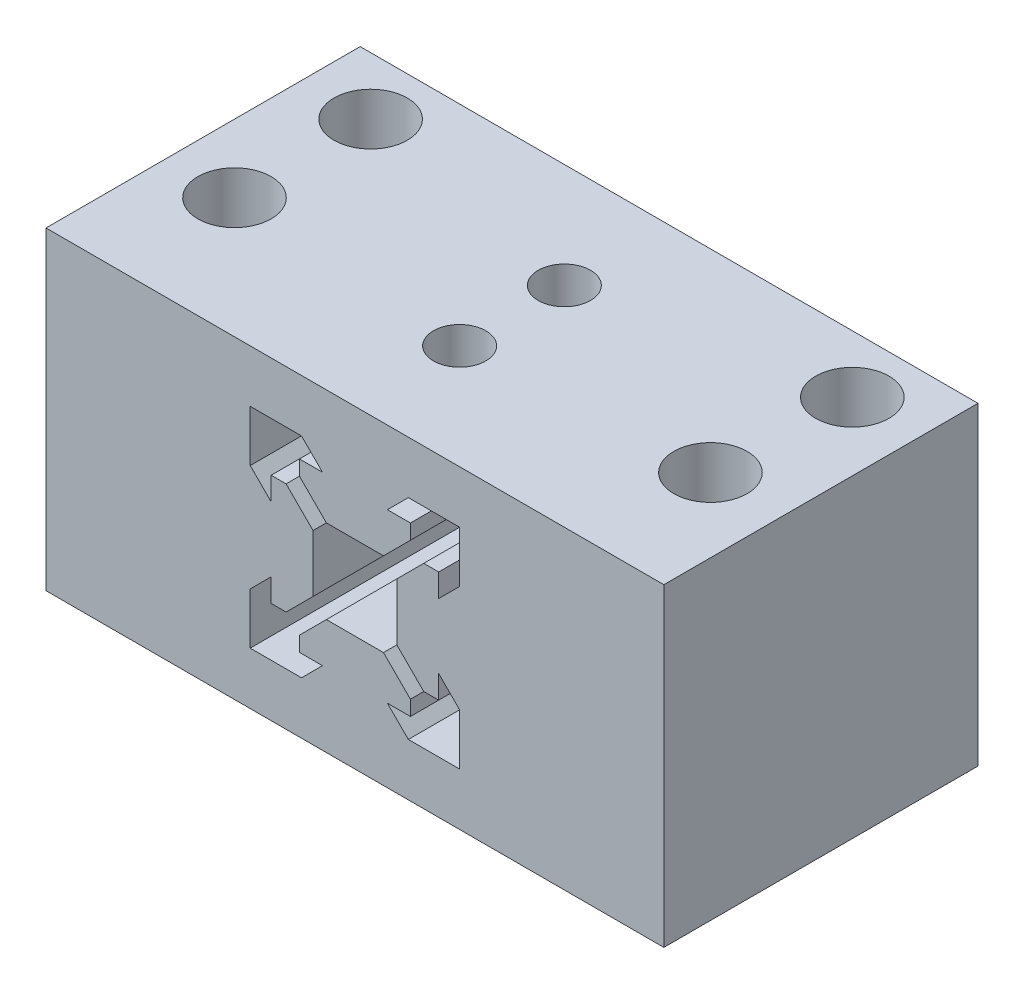
SolidWorks part; units mm, degrees
ref_plane "Front Plane" through (0, 0, 0) normal (0, 0, 1) x (1, 0, 0)
ref_plane "Top Plane" through (0, 0, 0) normal (0, 1, 0) x (1, 0, 0)
ref_plane "Right Plane" through (0, 0, 0) normal (1, 0, 0) x (0, 0, -1)
sketch "Sketch1" plane through (0, 0, 0) normal (0, 0, 1) x (1, 0, 0)
  line L1 (-29.5, 15) -> (29.5, 15)
  line L2 (-29.5, 15) -> (-29.5, -15)
  line L3 (-29.5, -15) -> (29.5, -15)
  line L4 (29.5, 15) -> (29.5, -15)
  line L5 (-29.5, 15) -> (29.5, -15) construction
  line L6 (-29.5, -15) -> (29.5, 15) construction
  line L90 (4, 2.7272) -> (6.5728, 5.3)
  line L91 (6.5728, 5.3) -> (8, 5.3)
  line L92 (8, 5.3) -> (8, 3.1)
  line L93 (8, 3.1) -> (10, 5.1)
  line L94 (10, 5.1) -> (10, 10)
  line L95 (10, 10) -> (5.1, 10)
  line L96 (5.1, 10) -> (3.1, 8)
  line L97 (3.1, 8) -> (5.3, 8)
  line L98 (5.3, 8) -> (5.3, 6.5728)
  line L99 (5.3, 6.5728) -> (2.7272, 4)
  line L100 (2.7272, 4) -> (-2.7272, 4)
  line L101 (-2.7272, 4) -> (-5.3, 6.5728)
  line L102 (-5.3, 6.5728) -> (-5.3, 8)
  line L103 (-5.3, 8) -> (-3.1, 8)
  line L104 (-3.1, 8) -> (-5.1, 10)
  line L105 (-5.1, 10) -> (-10, 10)
  line L106 (-10, 10) -> (-10, 5.1)
  line L107 (-10, 5.1) -> (-8, 3.1)
  line L108 (-8, 3.1) -> (-8, 5.3)
  line L109 (-8, 5.3) -> (-6.5728, 5.3)
  line L110 (-6.5728, 5.3) -> (-4, 2.7272)
  line L111 (-4, 2.7272) -> (-4, -2.7272)
  line L112 (-4, -2.7272) -> (-6.5728, -5.3)
  line L113 (-6.5728, -5.3) -> (-8, -5.3)
  line L114 (-8, -5.3) -> (-8, -3.1)
  line L115 (-8, -3.1) -> (-10, -5.1)
  line L116 (-10, -5.1) -> (-10, -10)
  line L117 (-10, -10) -> (-5.1, -10)
  line L118 (-5.1, -10) -> (-3.1, -8)
  line L119 (-3.1, -8) -> (-5.3, -8)
  line L120 (-5.3, -8) -> (-5.3, -6.5728)
  line L121 (-5.3, -6.5728) -> (-2.7272, -4)
  line L122 (-2.7272, -4) -> (2.7272, -4)
  line L123 (2.7272, -4) -> (5.3, -6.5728)
  line L124 (5.3, -6.5728) -> (5.3, -8)
  line L125 (5.3, -8) -> (3.1, -8)
  line L126 (3.1, -8) -> (5.1, -10)
  line L127 (5.1, -10) -> (10, -10)
  line L128 (10, -10) -> (10, -5.1)
  line L129 (10, -5.1) -> (8, -3.1)
  line L130 (8, -3.1) -> (8, -5.3)
  line L131 (8, -5.3) -> (6.5728, -5.3)
  line L132 (6.5728, -5.3) -> (4, -2.7272)
  line L133 (4, -2.7272) -> (4, 2.7272)
  point P2 (0, 0)
  dimension "D1" = 20
  dimension "D2" = 59
  dimension "D3" = 30
extrude "Boss-Extrude1" add sketch "Sketch1" against normal blind 30
sketch "Sketch2" plane through (0, 15, 0) normal (0, 1, 0) x (1, 0, 0)
  line L0 (-29.5, 30) -> (-29.5, 0) construction
  circle A0 centre (0, 10) radius 2.5
  circle A1 centre (0, 20) radius 2.5
  circle A2 centre (-23, 24.5) radius 3.5
  circle A4 centre (23, 24.5) radius 3.5
  circle A7 centre (22.4507, 11.5) radius 3.5
  circle A9 centre (-23, 11.5) radius 3.5
  dimension "D1" = 10
  dimension "D3" = 46
  dimension "D2" = 10
  dimension "D4" = 13
  dimension "D5" = 6.5
  dimension "D6" = 5.5
extrude "Cut-Extrude1" cut sketch "Sketch2" against normal through all
